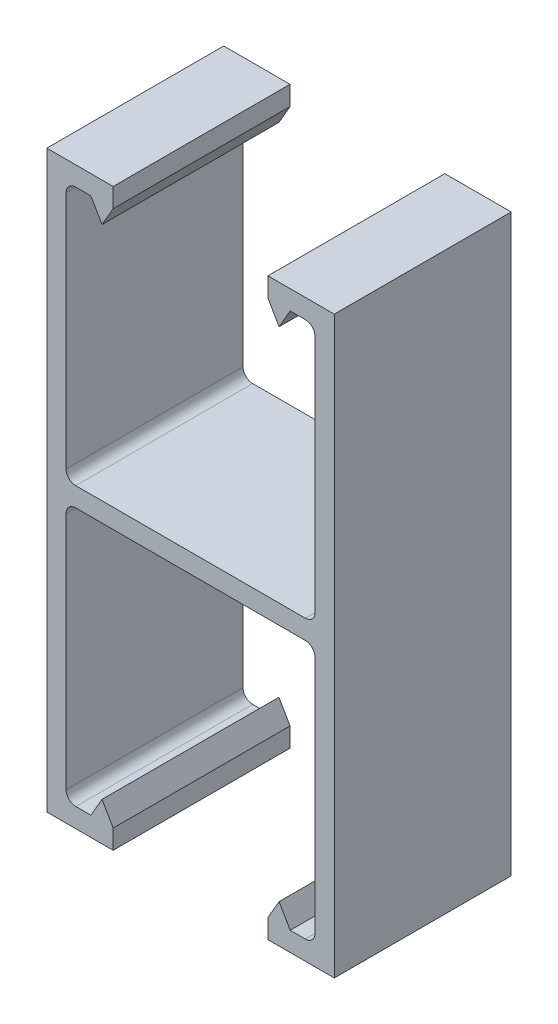
SolidWorks part; units mm, degrees
ref_plane "Plane1" through (0, 0, 0) normal (0, 0, 1) x (1, 0, 0)
ref_plane "Plane2" through (0, 0, 0) normal (0, 1, 0) x (1, 0, 0)
ref_plane "Plane3" through (0, 0, 0) normal (1, 0, 0) x (0, 0, -1)
sketch "Sketch1" plane through (0, 0, 0) normal (0, 0, 1) x (1, 0, 0)
  line L0 (-11.1125, 41.275) -> (-20.6375, 41.275)
  line L1 (-20.6375, 41.275) -> (-20.6375, -41.275)
  line L2 (-14.3094, -38.5064) -> (-16.4846, -38.5064)
  line L3 (20.6375, -41.275) -> (20.6375, 41.275)
  line L4 (20.6375, 41.275) -> (11.1125, 41.275)
  line L5 (16.4846, 38.5064) -> (14.3094, 38.5064)
  line L6 (17.8689, 2.7686) -> (17.8689, 37.1221)
  line L7 (-16.4846, 1.3843) -> (16.4846, 1.3843)
  line L8 (-17.8689, 37.1221) -> (-17.8689, 2.7686)
  line L9 (-14.3094, 38.5064) -> (-16.4846, 38.5064)
  line L10 (14.3094, 38.5064) -> (12.711, 35.7378)
  line L11 (12.711, 35.7378) -> (11.1125, 38.5064)
  line L12 (11.1125, 38.5064) -> (11.1125, 41.275)
  line L13 (-14.3094, 38.5064) -> (-12.711, 35.7378)
  line L14 (-12.711, 35.7378) -> (-11.1125, 38.5064)
  line L15 (-11.1125, 38.5064) -> (-11.1125, 41.275)
  line L16 (22.86, 0) -> (-25.4, 0) construction
  line L17 (12.711, -35.7378) -> (11.1125, -38.5064)
  line L18 (14.3094, -38.5064) -> (12.711, -35.7378)
  line L19 (16.4846, -38.5064) -> (14.3094, -38.5064)
  line L20 (20.6375, -41.275) -> (11.1125, -41.275)
  line L21 (11.1125, -38.5064) -> (11.1125, -41.275)
  line L22 (-11.1125, -41.275) -> (-20.6375, -41.275)
  line L23 (-11.1125, -38.5064) -> (-11.1125, -41.275)
  line L24 (-12.711, -35.7378) -> (-11.1125, -38.5064)
  line L25 (-14.3094, -38.5064) -> (-12.711, -35.7378)
  line L26 (-17.8689, -37.1221) -> (-17.8689, -2.7686)
  line L27 (17.8689, -2.7686) -> (17.8689, -37.1221)
  line L28 (-16.4846, -1.3843) -> (16.4846, -1.3843)
  arc A0 (-17.8689, 2.7686) -> (-16.4846, 1.3843) centre (-16.4846, 2.7686) ccw
  arc A1 (-16.4846, 38.5064) -> (-17.8689, 37.1221) centre (-16.4846, 37.1221) ccw
  arc A2 (17.8689, 37.1221) -> (16.4846, 38.5064) centre (16.4846, 37.1221) ccw
  arc A3 (16.4846, 1.3843) -> (17.8689, 2.7686) centre (16.4846, 2.7686) ccw
  arc A4 (17.8689, -37.1221) -> (16.4846, -38.5064) centre (16.4846, -37.1221) cw
  arc A5 (-16.4846, -38.5064) -> (-17.8689, -37.1221) centre (-16.4846, -37.1221) cw
  arc A6 (16.4846, -1.3843) -> (17.8689, -2.7686) centre (16.4846, -2.7686) cw
  arc A7 (-17.8689, -2.7686) -> (-16.4846, -1.3843) centre (-16.4846, -2.7686) cw
  dimension "D5" = 1.3843
  dimension "Width" = 41.275
  dimension "D8" = 20.6375
  dimension "D10" = 22.225
  dimension "edge" = 9.525
  dimension "D13" = 1.5985
  dimension "Height" = 82.55
  dimension "D3" = 41.275
  dimension "D4" = 60
extrude "Base-Extrude" add sketch "Sketch1" along normal mid plane 25.4
equation "\"D8@Sketch1\" = \"Width@Sketch1\" / 2"
equation "\"D10@Sketch1\" = \"Width@Sketch1\" - 2 * \"edge@Sketch1\""
equation "\"D5@Sketch1\" = \"gauge@Sketch1\" / 2"
equation "\"D3@Sketch1\" = \"Height@Sketch1\" / 2"
equation "\"D13@Sketch1\" = \"gauge@Sketch1\" * .577350269"
